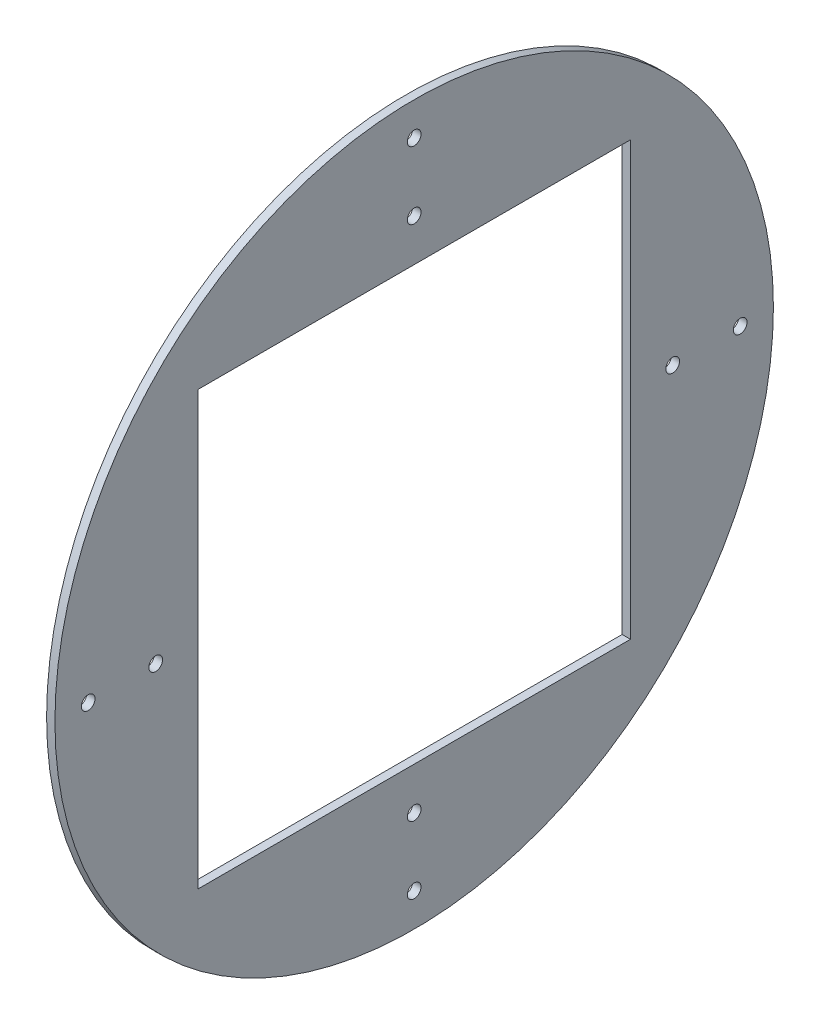
SolidWorks part; units mm, degrees
ref_plane "Front Plane" through (0, 0, 0) normal (1, 0, 0) x (0, 1, 0)
ref_plane "Top Plane" through (0, 0, 0) normal (0, 0, 1) x (0, 1, 0)
ref_plane "Right Plane" through (0, 0, 0) normal (0, 1, 0) x (-1, 0, 0)
sketch "Sketch1" plane through (0, 0, 0) normal (1, 0, 0) x (0, 1, 0)
  circle A0 centre (0, 0) radius 86.487
  circle A1 centre (0, 0) radius 52.07
  dimension "D1" = 172.974
  dimension "D2" = 104.14
extrude "Boss-Extrude1" add sketch "Sketch1" along normal blind 2.0066 contours A0
sketch "Sketch6" plane through (2.0066, 0, 0) normal (1, 0, 0) x (0, 0, -1)
  line L1 (52.07, 52.07) -> (-52.07, 52.07)
  line L2 (52.07, 52.07) -> (52.07, -52.07)
  line L3 (52.07, -52.07) -> (-52.07, -52.07)
  line L4 (-52.07, 52.07) -> (-52.07, -52.07)
  line L5 (52.07, 52.07) -> (-52.07, -52.07) construction
  line L6 (52.07, -52.07) -> (-52.07, 52.07) construction
  point P0 (0, 0)
  dimension "D1" = 104.14
  dimension "D2" = 104.14
extrude "Cut-Extrude2" cut sketch "Sketch6" against normal through all contours L2 L1 L4 L3
sketch "Sketch7" plane through (2.0066, 0, 0) normal (1, 0, 0) x (0, 1, 0)
  line L0 (52.07, 0) -> (62.23, 0)
  line L1 (52.07, -52.07) -> (52.07, 52.07) construction
  line L2 (62.23, 0) -> (78.486, 0)
  circle A0 centre (62.23, 0) radius 1.651
  circle A1 centre (78.486, 0) radius 1.651
  dimension "D2" = 3.302
  dimension "D4" = 3.302
  dimension "D1" = 10.16
  dimension "D3" = 16.256
extrude "Cut-Extrude3" cut sketch "Sketch7" against normal through all contours A1 | A0
pattern_circular "CirPattern1" count 4 over 360 about axis through (0, 0, 0) along (1, 0, 0) of "Cut-Extrude3"
